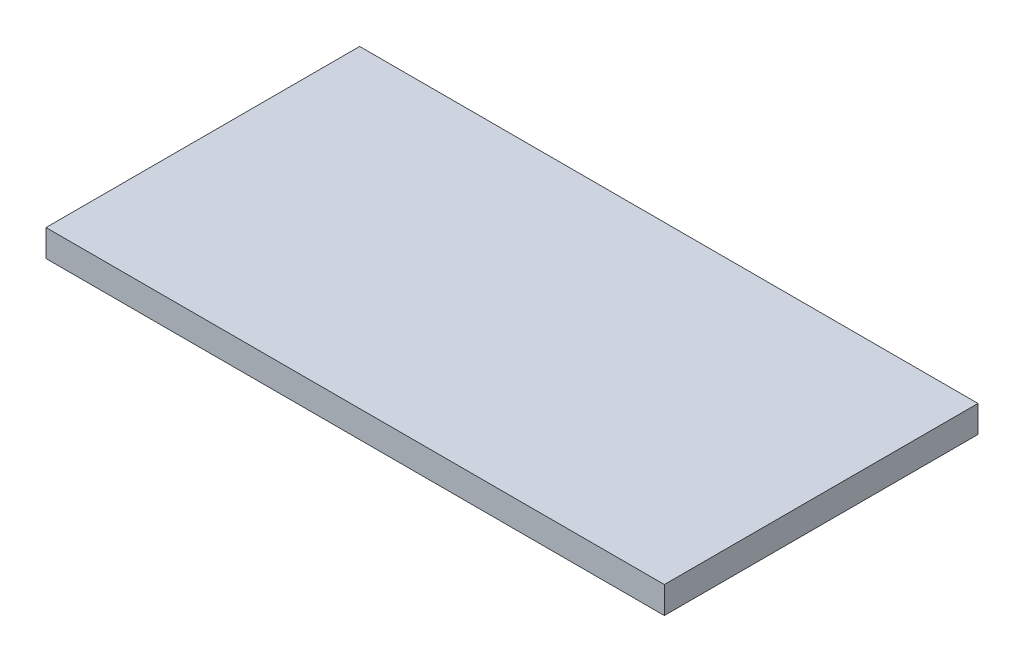
SolidWorks part; units mm, degrees
ref_plane "Front Plane" through (0, 0, 0) normal (0, 0, 1) x (1, 0, 0)
ref_plane "Top Plane" through (0, 0, 0) normal (0, 1, 0) x (1, 0, 0)
ref_plane "Right Plane" through (0, 0, 0) normal (1, 0, 0) x (0, 0, -1)
sketch "Sketch1" plane through (0, 0, 0) normal (0, 1, 0) x (1, 0, 0)
  line L1 (-34.5, 17.5) -> (34.5, 17.5)
  line L2 (-34.5, 17.5) -> (-34.5, -17.5)
  line L3 (-34.5, -17.5) -> (34.5, -17.5)
  line L4 (34.5, 17.5) -> (34.5, -17.5)
  line L5 (-34.5, 17.5) -> (34.5, -17.5) construction
  line L6 (-34.5, -17.5) -> (34.5, 17.5) construction
  point P0 (0, 0)
  dimension "D1" = 69
  dimension "D2" = 35
extrude "Boss-Extrude1" add sketch "Sketch1" along normal blind 3
